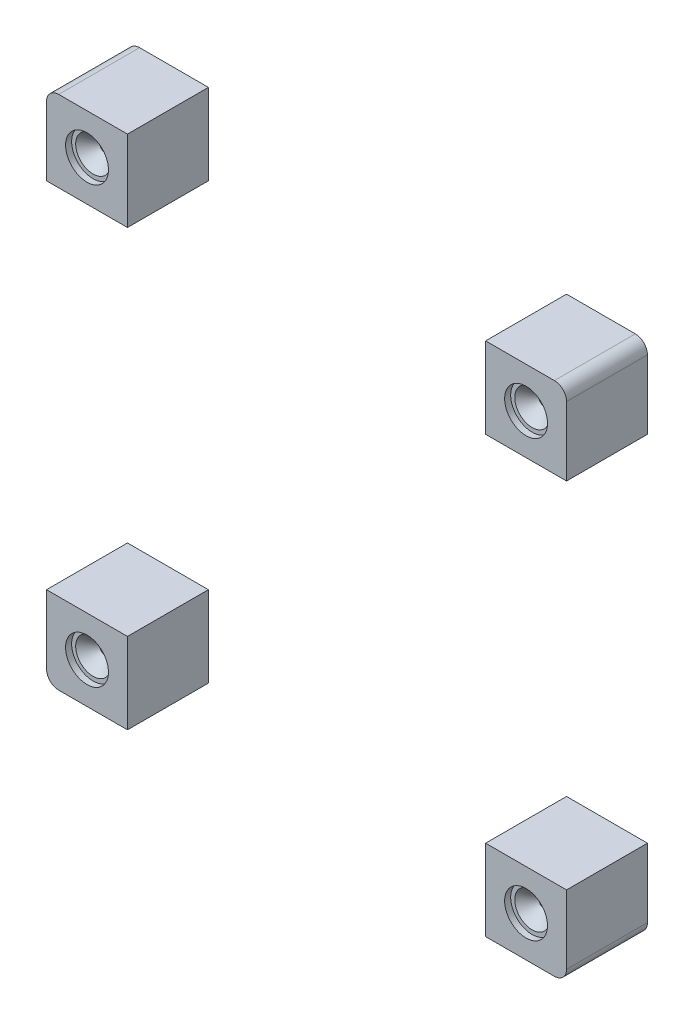
SolidWorks part; units mm, degrees
ref_plane "Спереди" through (0, 0, 0) normal (0, 0, 1) x (1, 0, 0)
ref_plane "Сверху" through (0, 0, 0) normal (0, 1, 0) x (1, 0, 0)
ref_plane "Справа" through (0, 0, 0) normal (1, 0, 0) x (0, 0, -1)
sketch "Эскиз1" plane through (0, 0, 0) normal (0, 0, 1) x (1, 0, 0)
  line L0 (-44.25, -43.75) -> (-64.25, -43.75)
  line L1 (-44.25, -43.75) -> (-44.25, -63.75)
  line L2 (0, 0) -> (0, -75.4217) construction
  line L3 (84.2244, 0) -> (84.1054, 0) construction
  line L4 (84.1054, 0) -> (0, 0) construction
  line L5 (44.25, -43.75) -> (44.25, -63.75)
  line L6 (44.25, -43.75) -> (64.25, -43.75)
  line L7 (44.25, 43.75) -> (44.25, 63.75)
  line L8 (64.25, -60.75) -> (64.25, -43.75)
  line L9 (61.25, 63.75) -> (44.25, 63.75)
  line L10 (-64.25, 60.75) -> (-64.25, 43.75)
  line L11 (-61.25, -63.75) -> (-44.25, -63.75)
  line L12 (44.25, 43.75) -> (64.25, 43.75)
  line L13 (-44.25, 43.75) -> (-64.25, 43.75)
  line L14 (-44.25, 43.75) -> (-44.25, 63.75)
  line L15 (-44.25, 63.75) -> (-61.25, 63.75)
  line L16 (64.25, 43.75) -> (64.25, 60.75)
  line L17 (44.25, -63.75) -> (61.25, -63.75)
  line L18 (-64.25, -43.75) -> (-64.25, -60.75)
  arc A8 (64.25, 60.75) -> (61.25, 63.75) centre (61.25, 60.75) ccw
  arc A9 (-61.25, 63.75) -> (-64.25, 60.75) centre (-61.25, 60.75) ccw
  arc A10 (-64.25, -60.75) -> (-61.25, -63.75) centre (-61.25, -60.75) ccw
  arc A11 (61.25, -63.75) -> (64.25, -60.75) centre (61.25, -60.75) ccw
  point P2 (-64.25, -43.75)
  point P3 (-44.25, -63.75)
  point P6 (-44.25, -43.75)
extrude "Бобышка-Вытянуть1" add sketch "Эскиз1" along normal blind 20
sketch "Эскиз2" plane through (0, 0, 20) normal (0, 0, 1) x (1, 0, 0)
  circle A4 centre (54.25, 53.75) radius 1.3
  circle A5 centre (-54.25, 53.75) radius 1.3
  circle A6 centre (-54.25, -53.75) radius 1.3
  circle A7 centre (54.25, -53.75) radius 1.3
extrude "Вырез-Вытянуть1" cut sketch "Эскиз2" against normal blind 21
sketch "Эскиз3" plane through (0, 0, 20) normal (0, 0, 1) x (1, 0, 0)
  circle A21 centre (-54.25, 53.75) radius 5.3
  circle A22 centre (-54.25, 53.75) radius 5.3
  circle A24 centre (54.25, 53.75) radius 5.3
  circle A25 centre (54.25, 53.75) radius 5.3
  circle A27 centre (54.25, -53.75) radius 5.3
  circle A28 centre (54.25, -53.75) radius 5.3
  circle A30 centre (-54.25, -53.75) radius 5.3
  circle A31 centre (-54.25, -53.75) radius 5.3
  dimension "D1" = 4
  dimension "D2" = 4
  dimension "D3" = 4
  dimension "D4" = 4
extrude "Вырез-Вытянуть2" cut sketch "Эскиз3" against normal blind 1.5
chamfer "Фаска1" distance 3 angle 45 1 edges at (-52.95, 53.75, 18.5)
chamfer "Фаска2" distance 3 angle 45 1 edges at (-52.95, -53.75, 18.5)
chamfer "Фаска3" distance 3 angle 45 1 edges at (55.55, 53.75, 18.5)
chamfer "Фаска4" distance 3 angle 45 1 edges at (55.55, -53.75, 18.5)
